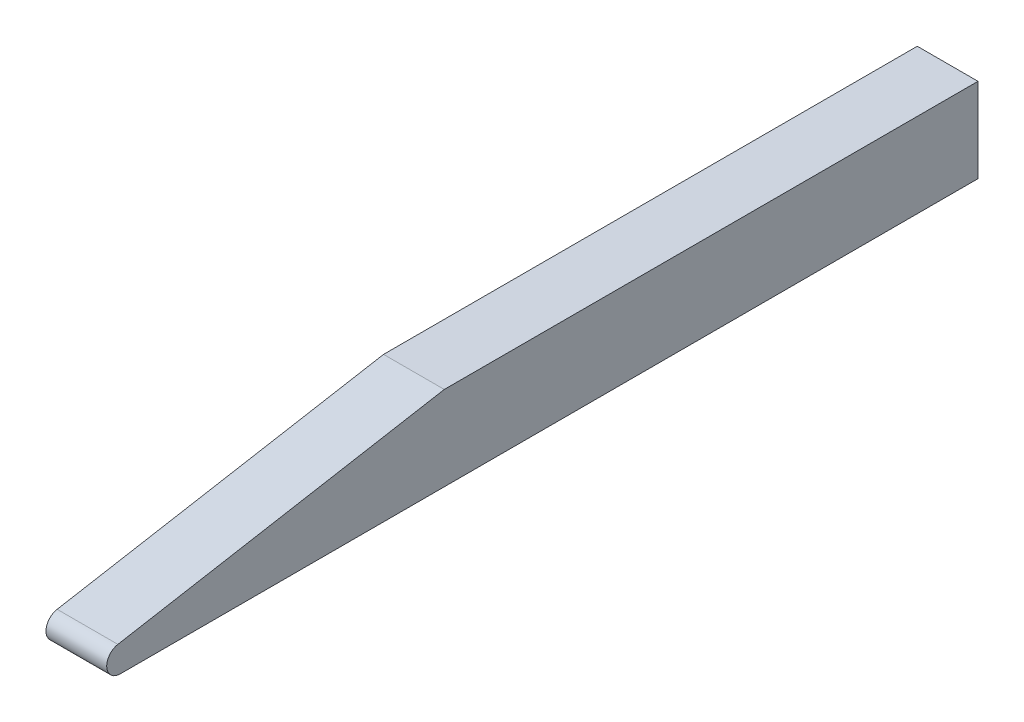
SolidWorks part; units mm, degrees
ref_plane "Front Plane" through (0, 0, 0) normal (0, 0, 1) x (1, 0, 0)
ref_plane "Top Plane" through (0, 0, 0) normal (0, 1, 0) x (1, 0, 0)
ref_plane "Right Plane" through (0, 0, 0) normal (1, 0, 0) x (0, 0, -1)
sketch "Sketch1" plane through (0, 0, 0) normal (1, 0, 0) x (0, 0, -1)
  line L0 (0, 0) -> (7.0891, 1.25)
  line L1 (7.0891, 1.25) -> (15, 1.25)
  line L2 (15, 1.25) -> (15, 0)
  line L3 (15, 0) -> (0, 0)
  dimension "D1" = 1.25
  dimension "D2" = 10
  dimension "D3" = 15
extrude "Boss-Extrude1" add sketch "Sketch1" along normal mid plane 0.9
fillet "Fillet1" radius 0.2 1 edges at (0, 0, 0)
